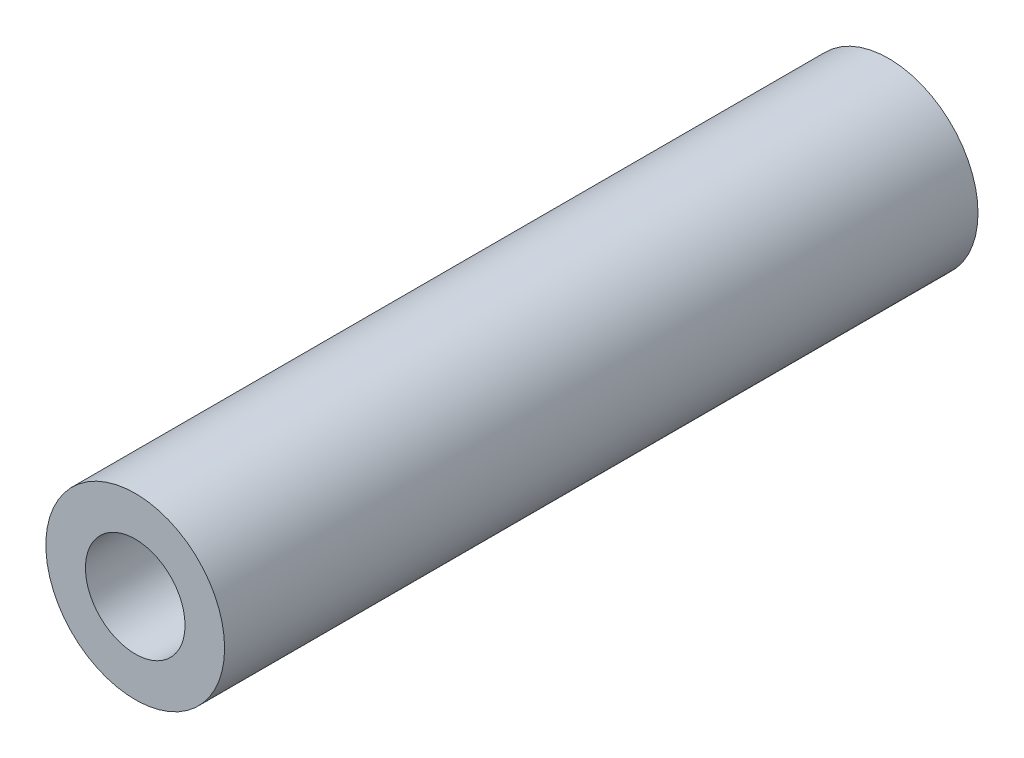
SolidWorks part; units mm, degrees
ref_plane "Plan de face" through (0, 0, 0) normal (0, 0, 1) x (1, 0, 0)
ref_plane "Plan de dessus" through (0, 0, 0) normal (0, 1, 0) x (1, 0, 0)
ref_plane "Plan de droite" through (0, 0, 0) normal (1, 0, 0) x (0, 0, -1)
sketch "Esquisse1" plane through (0, 0, 0) normal (0, 0, 1) x (1, 0, 0)
  circle A0 centre (0, 0) radius 3.5
  dimension "D1" = 7
extrude "Boss.-Extru.1" add sketch "Esquisse1" along normal blind 29.5
hole_wizard "Trou pour taraudage pour trou taraudé M41" positions "Esquisse2" profile "Esquisse3" hole size "M4" standard "ISO" end condition through all
sketch "Esquisse2" plane through (0, 0, 29.5) normal (0, 0, 1) x (1, 0, 0)
  point P0 (0, 0)
sketch "Esquisse3" plane through (0, 0, 29.5) normal (1, 0, 0) x (0, -1, 0)
  line L0 (0, 0) -> (0, 29.5)
  line L1 (0, 29.5) -> (1.95, 29.5)
  line L2 (1.95, 29.5) -> (1.95, 0)
  line L5 (1.95, 0) -> (0, 0)
  line L11 (0, -6.35) -> (0, 107.95) construction
  dimension "Diamètre du perçage jusqu'au prochain" = 3.9
  dimension "Profondeur du perçage jusqu'au prochain" = 29.5
